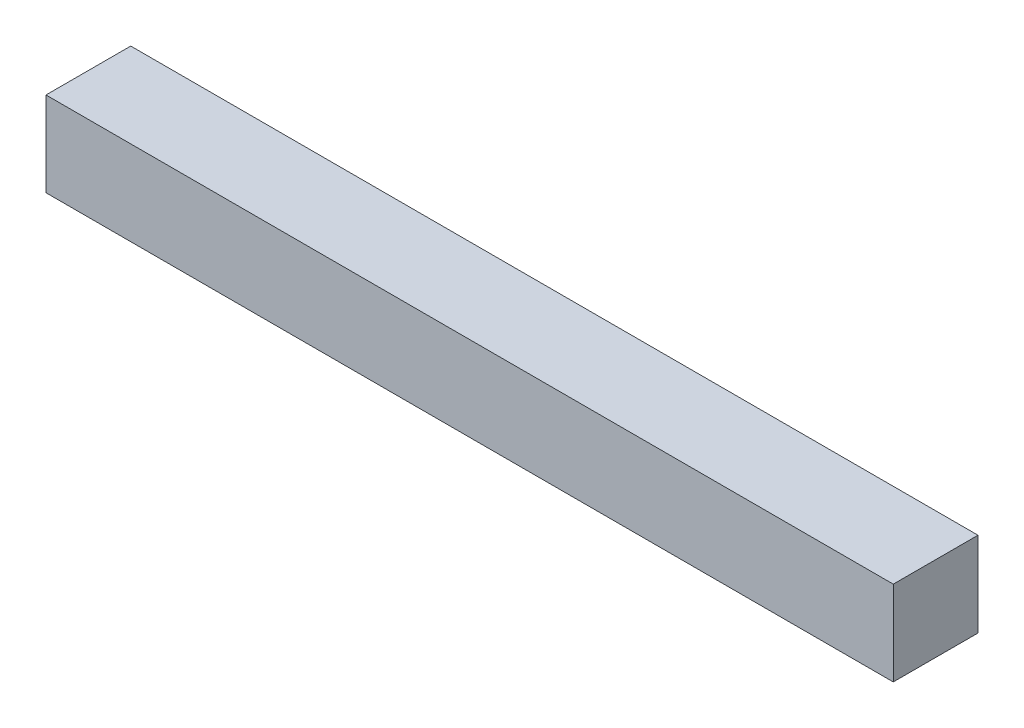
SolidWorks part; units mm, degrees
ref_plane "Přední rovina" through (0, 0, 0) normal (0, 0, 1) x (1, 0, 0)
ref_plane "Horní rovina" through (0, 0, 0) normal (0, 1, 0) x (1, 0, 0)
ref_plane "Pravá rovina" through (0, 0, 0) normal (1, 0, 0) x (0, 0, -1)
sketch "Sketch1" plane through (0, 0, 0) normal (0, 0, 1) x (1, 0, 0)
  line L1 (0, 0) -> (100, 0)
  line L2 (0, 0) -> (0, 10)
  line L3 (0, 10) -> (100, 10)
  line L4 (100, 0) -> (100, 10)
  dimension "D1" = 100
  dimension "D2" = 10
extrude "Boss-Extrude1" add sketch "Sketch1" along normal blind 10
